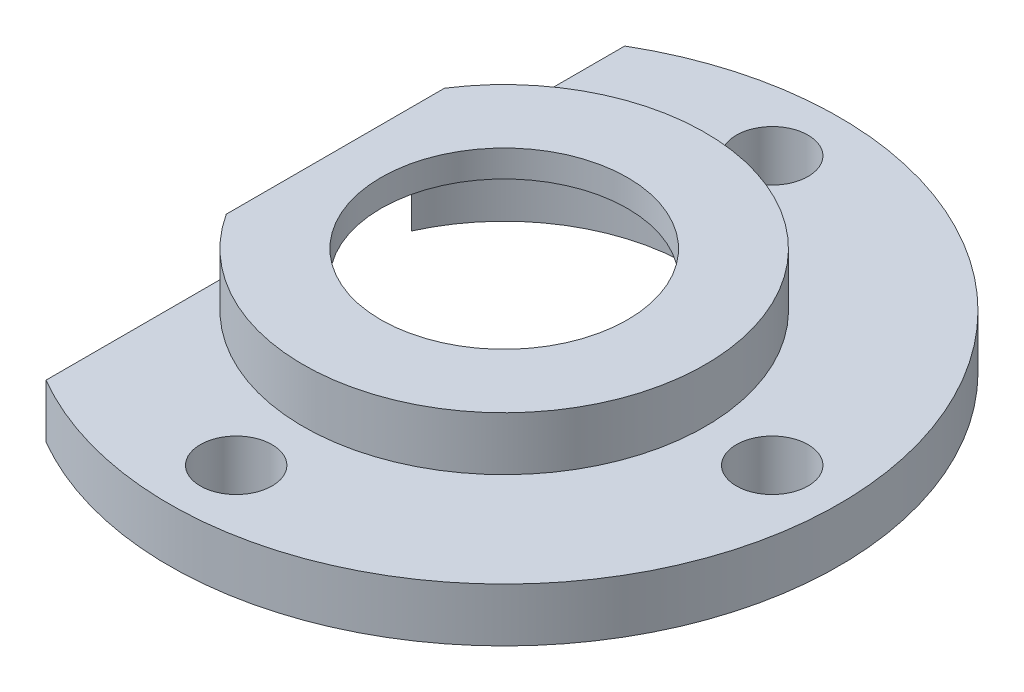
SolidWorks part; units mm, degrees
ref_plane "Front Plane" through (0, 0, 0) normal (0, 0, 1) x (1, 0, 0)
ref_plane "Top Plane" through (0, 0, 0) normal (0, 1, 0) x (1, 0, 0)
ref_plane "Right Plane" through (0, 0, 0) normal (1, 0, 0) x (0, 0, -1)
sketch "Sketch1" plane through (0, 0, 0) normal (0, 1, 0) x (1, 0, 0)
  circle A0 centre (0, 0) radius 15.875
  dimension "D1" = 31.75
extrude "Boss-Extrude1" add sketch "Sketch1" along normal blind 2.54
sketch "Sketch2" plane through (0, 2.54, 0) normal (0, 1, 0) x (1, 0, 0)
  circle A0 centre (0, 0) radius 9.525
  dimension "D1" = 19.05
extrude "Boss-Extrude2" add sketch "Sketch2" along normal blind 2.54
sketch "Sketch3" plane through (0, 0, 0) normal (0, -1, 0) x (1, 0, 0)
  circle A0 centre (0, 0) radius 8.7757
  dimension "D1" = 17.5514
extrude "Cut-Extrude1" cut sketch "Sketch3" against normal blind 3.81
sketch "Sketch4" plane through (0, 5.08, 0) normal (0, 1, 0) x (1, 0, 0)
  circle A0 centre (0, 0) radius 5.842
  dimension "D1" = 11.684
extrude "Cut-Extrude2" cut sketch "Sketch4" against normal up to next
sketch "Sketch5" plane through (0, 2.54, 0) normal (0, 1, 0) x (1, 0, 0)
  line L0 (0, 15.875) -> (0, 0) construction
  circle A0 centre (0, 12.7) radius 1.7
  circle A1 centre (0, 0) radius 15.875 construction
  circle A2 centre (12.7, 0) radius 1.7
  circle A3 centre (0, -12.7) radius 1.7
  circle A4 centre (-12.7, 0) radius 1.7
  point P18 (0, 0)
  dimension "D2" = 3.4
  dimension "D1" = 12.7
  dimension "D3" = 4
extrude "Cut-Extrude3" cut sketch "Sketch5" against normal up to next
sketch "Sketch6" plane through (0, 2.54, 0) normal (0, 1, 0) x (1, 0, 0)
  line L0 (-8, -13.7119) -> (-8, 13.7119)
  circle A1 centre (0, 0) radius 15.875 construction
  arc A2 (-8, -13.7119) -> (-8, 13.7119) centre (0, 0) cw
  circle M4 centre (-12.7, 0) radius 1.7
  circle M5 centre (0, 0) radius 9.525
  circle M6 centre (0, 0) radius 15.875
  dimension "D1" = 8
extrude "Cut-Extrude5" cut sketch "Sketch6" against normal up to next and the other way blind 2.794 contours L0 M5 | L0 M6 M5 M4
